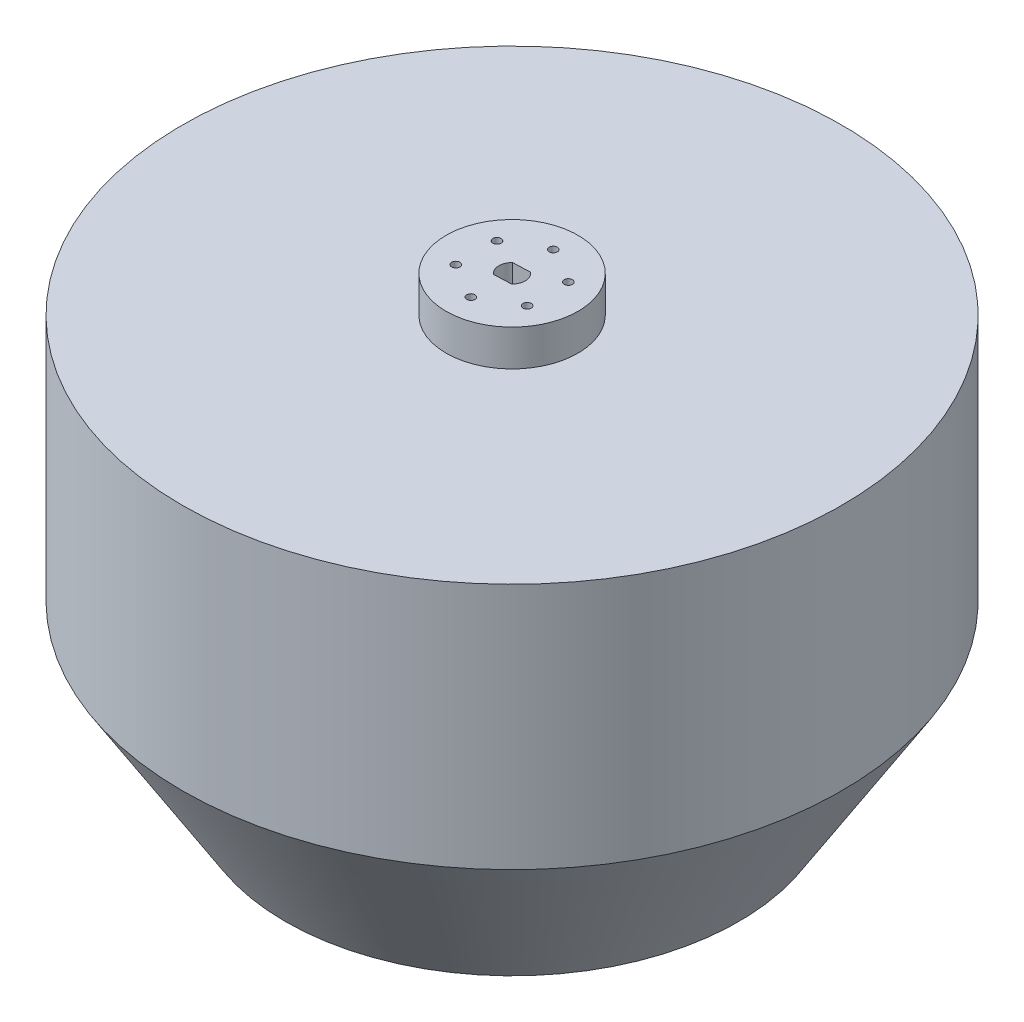
SolidWorks part; units mm, degrees
ref_plane "Front Plane" through (0, 0, 0) normal (0, 0, 1) x (1, 0, 0)
ref_plane "Top Plane" through (0, 0, 0) normal (0, 1, 0) x (1, 0, 0)
ref_plane "Right Plane" through (0, 0, 0) normal (1, 0, 0) x (0, 0, -1)
sketch "Sketch2" plane through (0, 0, 0) normal (0, 0, 1) x (1, 0, 0)
  line L0 (0, 57.3493) -> (0, -66.5497) construction
  line L1 (0, 45.2295) -> (-200, 45.2295)
  line L2 (-200, 45.2295) -> (-200, -104.7705)
  line L3 (-200, -104.7705) -> (-137.5, -204.7705)
  line L4 (-137.5, -204.7705) -> (-117.5, -204.7705)
  line L5 (-117.5, -204.7705) -> (-180, -104.7705)
  line L6 (-180, -104.7705) -> (-180, 25.2295)
  line L7 (-180, 25.2295) -> (-97.5, 25.2295)
  line L8 (0, 25.2295) -> (0, 45.2295)
  line L9 (-97.5, 25.2295) -> (-97.5, -104.7705)
  line L10 (-97.5, -104.7705) -> (-35, -204.7705)
  line L11 (-35, -204.7705) -> (0, -204.7705)
  line L12 (0, -204.7705) -> (0, 25.2295)
  dimension "D1" = 20
  dimension "D2" = 200
  dimension "D3" = 20
  dimension "D4" = 20
  dimension "D5" = 150
  dimension "D6" = 100
  dimension "D7" = 97.5
  dimension "D8" = 35
  dimension "D9" = 82.5
revolve "Revolve1" add sketch "Sketch2" angle 360 about L0
sketch "Sketch3" plane through (0, 0, 0) normal (0, 0, 1) x (1, 0, 0)
  line L0 (0, 80.7285) -> (0, -227.5722) construction
  line L1 (-97.5, 25.2295) -> (180, 25.2295) construction
  line L2 (-180, 25.2295) -> (180, 25.2295) construction
  circle A16 centre (-107.8608, 4.2503) radius 12.5
  circle A17 centre (-107.8608, -9.7358) radius 12.5
  circle A18 centre (-107.8608, -23.722) radius 12.5
  circle A19 centre (-107.8608, -37.7081) radius 12.5
  circle A20 centre (-107.8608, -51.6942) radius 12.5
  circle A21 centre (-107.8608, -65.6804) radius 12.5
  circle A22 centre (-107.8608, -79.6665) radius 12.5
  circle A23 centre (-107.8608, -93.6526) radius 12.5
  dimension "D2" = 25
  dimension "D1" = 97.5
revolve "Cut-Revolve1" cut sketch "Sketch3" angle 360 about L0
sketch "Sketch4" plane through (0, 0, 0) normal (0, 0, 1) x (1, 0, 0)
  line L2 (0, 86.0646) -> (0, -290.0279) construction
  circle A0 centre (-99.4467, -117.118) radius 12.5
  circle A1 centre (-89.4415, -133.1263) radius 12.5
  circle A2 centre (-79.4363, -149.1347) radius 12.5
  circle A3 centre (-69.431, -165.143) radius 12.5
  circle A4 centre (-59.4258, -181.1514) radius 12.5
  circle A5 centre (-49.4206, -197.1597) radius 12.5
  dimension "D1" = 25
revolve "Cut-Revolve2" cut sketch "Sketch4" angle 360 about L2
sketch "Sketch5" plane through (0, 45.2295, 0) normal (0, 1, 0) x (1, 0, 0)
  line L0 (-5.5226, 5.7879) -> (5.0522, 6.2028)
  line L2 (5.5226, -5.7879) -> (-5.0522, -6.2028)
  circle A0 centre (0, 0) radius 40
  arc A1 (-5.5226, 5.7879) -> (-5.0522, -6.2028) centre (0, 0) ccw
  arc A2 (5.5226, -5.7879) -> (5.0522, 6.2028) centre (0, 0) ccw
  dimension "D1" = 80
extrude "Boss-Extrude1" add sketch "Sketch5" along normal blind 22
sketch "Sketch6" plane through (0, 67.2295, 0) normal (0, 1, 0) x (1, 0, 0)
  circle A0 centre (0, 0) radius 25 construction
  circle A7 centre (0, 25) radius 2.5
  circle A8 centre (21.6506, 12.5) radius 2.5
  circle A9 centre (21.6506, -12.5) radius 2.5
  circle A10 centre (0, -25) radius 2.5
  circle A11 centre (-21.6506, -12.5) radius 2.5
  circle A12 centre (-21.6506, 12.5) radius 2.5
  point P19 (1.4277, -33.8565)
  point P20 (0, 0)
  dimension "D1" = 5
  dimension "D2" = 6
extrude "Cut-Extrude1" cut sketch "Sketch6" against normal blind 15
